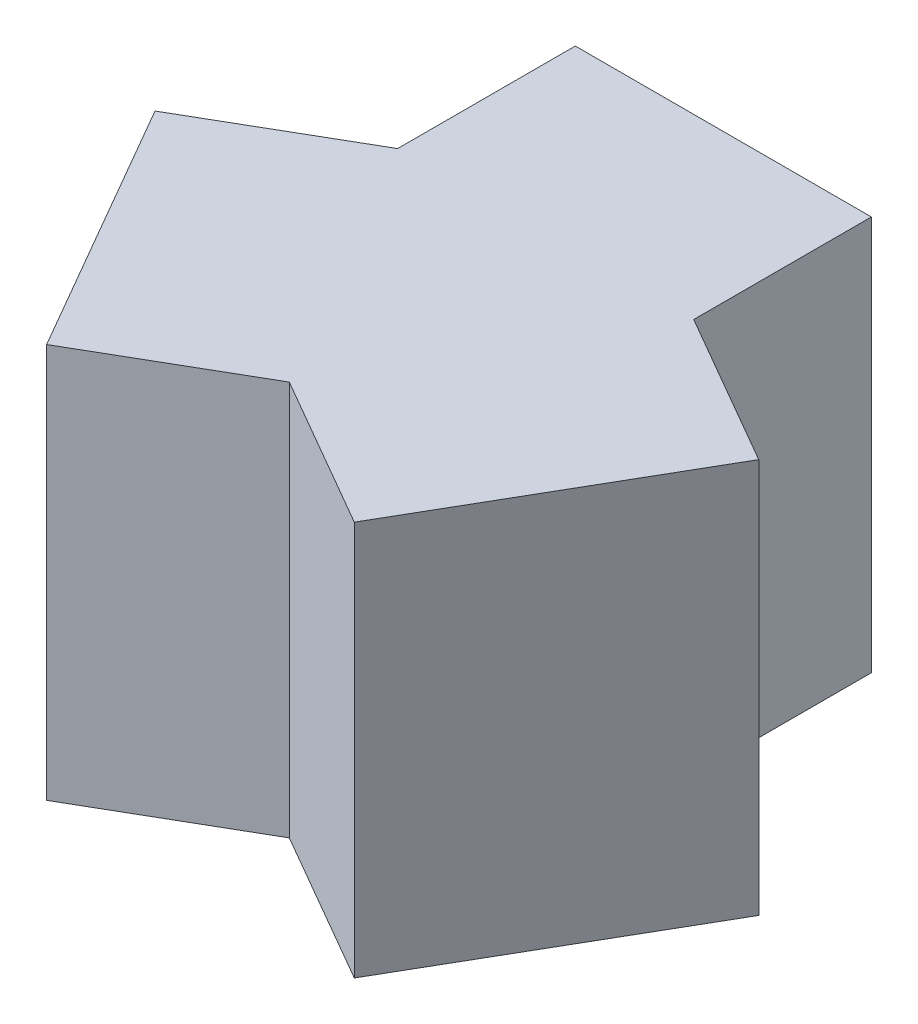
SolidWorks part; units mm, degrees
ref_plane "Front Plane" through (0, 0, 0) normal (0, 0, 1) x (1, 0, 0)
ref_plane "Top Plane" through (0, 0, 0) normal (0, 1, 0) x (1, 0, 0)
ref_plane "Right Plane" through (0, 0, 0) normal (1, 0, 0) x (0, 0, -1)
sketch "Sketch1" plane through (0, 0, 0) normal (0, 1, 0) x (1, 0, 0)
  line L0 (15.2942, 0.5) -> (7.5, 5)
  line L1 (7.5, 5) -> (7.5, 14)
  line L5 (0, -7.9904) -> (7.7942, -12.4904)
  line L7 (7.5, 5) -> (0, -7.9904) construction
  line L8 (7.5, 5) -> (-7.5, 5) construction
  line L9 (-7.5, 14) -> (7.5, 14)
  line L10 (15.2942, 0.5) -> (7.7942, -12.4904)
  line L12 (0, 30.0328) -> (0, -20.7177) construction
  line L13 (-7.5, 5) -> (0, -7.9904) construction
  line L14 (-15.2942, 0.5) -> (-7.7942, -12.4904)
  line L15 (0, -7.9904) -> (-7.7942, -12.4904)
  line L16 (-15.2942, 0.5) -> (-7.5, 5)
  line L17 (-7.5, 5) -> (-7.5, 14)
  point P6 (0, 5)
  point P9 (0, 14)
  dimension "D3" = 15
  dimension "D4" = 9
  dimension "D5" = 9
extrude "Boss-Extrude1" add sketch "Sketch1" along normal mid plane 20
